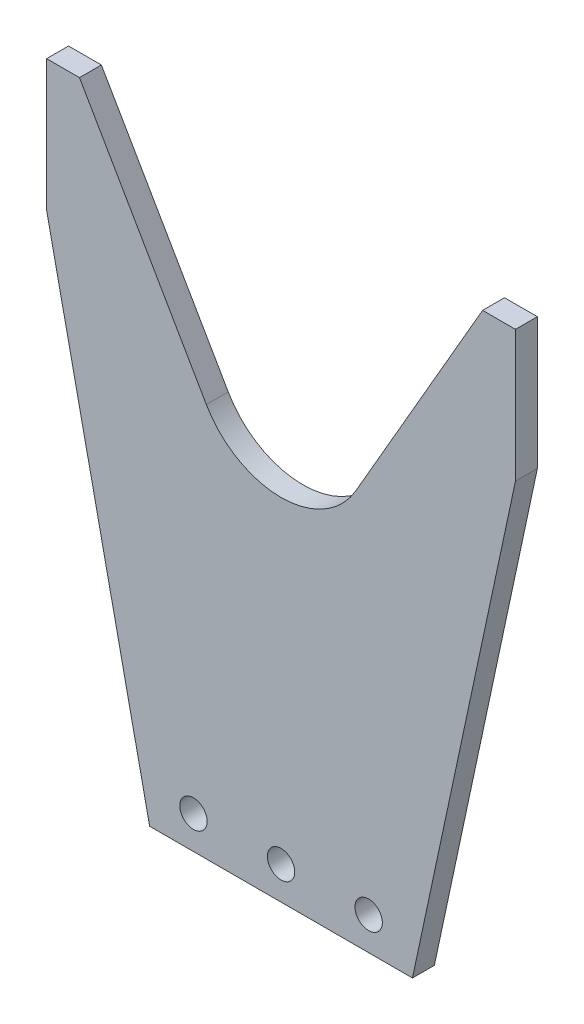
SolidWorks part; units mm, degrees
material "6061-T6 (SS)"
ref_plane "Front" through (0, 0, 0) normal (0, 0, 1) x (1, 0, 0)
ref_plane "Top" through (0, 0, 0) normal (0, 1, 0) x (1, 0, 0)
ref_plane "Right" through (0, 0, 0) normal (1, 0, 0) x (0, 0, -1)
sketch "Sketch1" plane through (0, 0, 0) normal (0, 0, 1) x (1, 0, 0)
  line L0 (-21.6671, -12.5095) -> (-58.4388, 51.181)
  line L1 (21.6671, -12.5095) -> (58.4388, 51.181)
  line L3 (-58.4388, 51.181) -> (-67.9638, 51.181)
  line L4 (-67.9638, 51.181) -> (-67.9638, 13.081)
  line L5 (-58.4388, 51.181) -> (58.4388, 51.181) construction
  line L6 (58.4388, 51.181) -> (67.9638, 51.181)
  line L7 (38.1, -126.619) -> (67.9638, 13.081)
  line L8 (38.1, -126.619) -> (-38.1, -126.619)
  line L9 (-38.1, -126.619) -> (-67.9638, 13.081)
  line L10 (67.9638, 51.181) -> (67.9638, 13.081)
  arc A0 (-21.6671, -12.5095) -> (21.6671, -12.5095) centre (0, 0) ccw
  point P9 (0, -25.019)
  dimension "D1" = 25.019
  dimension "D2" = 120
  dimension "D3" = 9.525
  dimension "D4" = 101.6
  dimension "D5" = 76.2
  dimension "D6" = 76.2
  dimension "D7" = 38.1
extrude "Boss-Extrude1" add sketch "Sketch1" along normal blind 6.35
sketch "Sketch2" plane through (0, 0, 6.35) normal (0, 0, 1) x (1, 0, 0)
  line L0 (0, -126.619) -> (0, -117.094) construction
  line L1 (-38.1, -126.619) -> (38.1, -126.619) construction
  line L2 (0, -117.094) -> (25.4, -117.094) construction
  line L3 (0, -117.094) -> (-25.4, -117.094) construction
  dimension "D1" = 9.525
  dimension "D2" = 50.8
hole_wizard "5/16 (0.3125) Diameter Hole1" positions "Sketch4" profile "Sketch3" hole size "5/16" standard "ANSI Inch" end condition through all
sketch "Sketch4" plane through (0, 0, 6.35) normal (0, 0, 1) x (1, 0, 0)
  point P0 (-25.4, -117.094)
  point P3 (25.4, -117.094)
  point P7 (0, -117.094)
sketch "Sketch3" plane through (-25.4, -117.094, 6.35) normal (1, 0, 0) x (0, -1, 0)
  line L0 (0, 0) -> (0, 6.35)
  line L1 (0, 6.35) -> (3.9687, 6.35)
  line L2 (3.9687, 6.35) -> (3.9687, 0)
  line L5 (3.9687, 0) -> (0, 0)
  line L11 (0, -6.35) -> (0, 107.95) construction
  dimension "Thru Hole Dia." = 7.9375
  dimension "Thru Hole Depth" = 6.35
